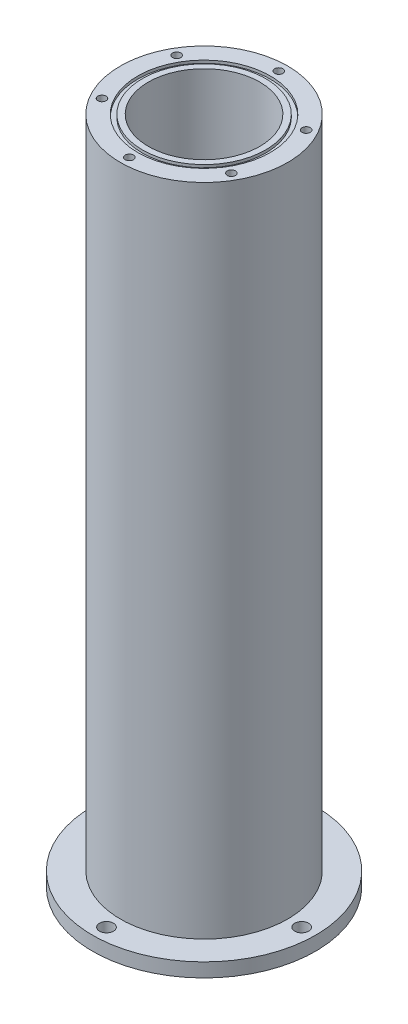
SolidWorks part; units mm, degrees
ref_plane "Front Plane" through (0, 0, 0) normal (0, 0, 1) x (1, 0, 0)
ref_plane "Top Plane" through (0, 0, 0) normal (0, 1, 0) x (1, 0, 0)
ref_plane "Right Plane" through (0, 0, 0) normal (1, 0, 0) x (0, 0, -1)
sketch "Sketch1" plane through (0, 0, 0) normal (0, 1, 0) x (1, 0, 0)
  circle A0 centre (0, 0) radius 25.4
  circle A1 centre (0, 0) radius 38.1
  dimension "D1" = 50.8
  dimension "D2" = 76.2
extrude "Boss-Extrude1" add sketch "Sketch1" along normal blind 304.8
sketch "Sketch2" plane through (0, 0, 0) normal (0, -1, 0) x (-1, 0, 0)
  circle A0 centre (0, 0) radius 50.8
  circle A2 centre (0, 0) radius 38.1 construction
  circle A3 centre (0, 0) radius 38.1
  dimension "D1" = 101.6
extrude "Boss-Extrude2" add sketch "Sketch2" against normal blind 6.35
hole_wizard "1/4 (0.25) Diameter Hole1" positions "Sketch4" profile "Sketch3" hole size "1/4" standard "ANSI Inch" end condition up to next
sketch "Sketch4" plane through (0, 0, 0) normal (0, -1, 0) x (-1, 0, 0)
  line L0 (0, -63.5) -> (0, 63.5) construction
  line L2 (63.5, 0) -> (-63.5, 0) construction
  point P0 (0, -44.45)
  point P2 (-44.45, 0)
  point P4 (0, 44.45)
  point P6 (44.45, 0)
  dimension "D1" = 44.45
  dimension "D2" = 44.45
  dimension "D3" = 44.45
  dimension "D4" = 44.45
sketch "Sketch3" plane through (0, 0, 44.45) normal (1, 0, 0) x (0, 0, -1)
  line L0 (0, 0) -> (0, 6.35)
  line L1 (0, 6.35) -> (3.175, 6.35)
  line L2 (3.175, 6.35) -> (3.175, 0)
  line L5 (3.175, 0) -> (0, 0)
  line L11 (0, -6.35) -> (0, 107.95) construction
  dimension "Thru Hole Dia." = 6.35
  dimension "Thru Hole Depth" = 6.35
sketch "Sketch5" plane through (0, 0, 0) normal (0, -1, 0) x (-1, 0, 0)
  circle A0 centre (0, 0) radius 28.6385
  dimension "D1" = 57.277
extrude "Cut-Extrude1" cut sketch "Sketch5" against normal blind 6.477
sketch "Sketch6" plane through (0, 304.8, 0) normal (0, 1, 0) x (1, 0, 0)
  circle A0 centre (0, 0) radius 30.2133
  circle A1 centre (0, 0) radius 38.1 construction
  circle A2 centre (0, 0) radius 28.1051
  dimension "D1" = 60.4266
  dimension "D2" = 56.2102
extrude "Cut-Extrude2" cut sketch "Sketch6" against normal blind 1.27
hole_wizard "Tapped Hole for #6-32 Helicoil1" positions "Sketch8" profile "Sketch7" tap size "#6-32" standard "Helicoil® Inch" end condition up to next
sketch "Sketch8" plane through (0, 304.8, 0) normal (0, 1, 0) x (1, 0, 0)
  line L0 (0, 0) -> (0, 50.8) construction
  point P0 (0, 34.036)
  dimension "D1" = 34.036
sketch "Sketch7" plane through (0, 304.8, -34.036) normal (1, 0, 0) x (0, 0, 1)
  line L0 (0, 0) -> (0, 304.801)
  line L1 (0, 304.801) -> (1.8669, 304.801)
  line L2 (1.8669, 304.801) -> (1.8669, 0)
  line L5 (1.8669, 0) -> (0, 0)
  line L11 (0, -6.35) -> (0, 107.95) construction
  dimension "Thru Tap Drill Dia." = 3.7338
  dimension "Thru Tap Drill Depth" = 304.801
cosmetic thread "Hole Thread1" parameters "D1"=4.318, "D2"=4.6152
pattern_circular "CirPattern1" count 6 over 360 about axis through (0, 0, 0) along (0, 1, 0) of "Tapped Hole for #6-32 Helicoil1"
